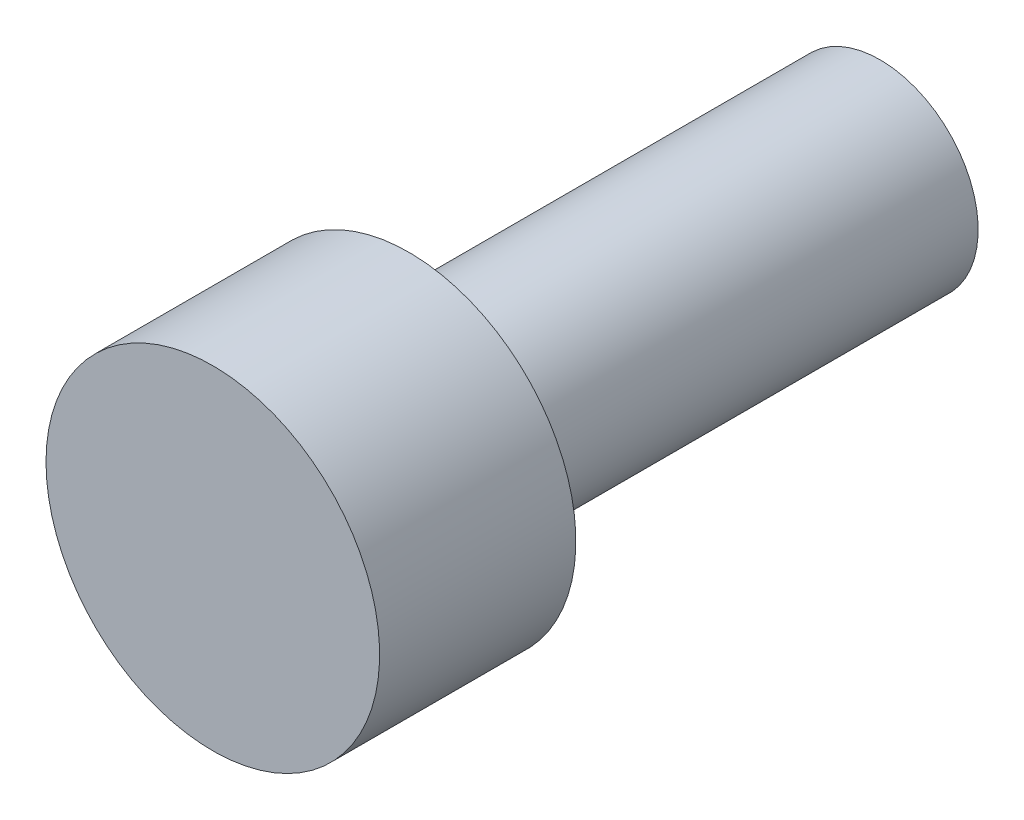
SolidWorks part; units mm, degrees
material "1.1191 (C45E)"
ref_plane "Front Plane" through (0, 0, 0) normal (0, 0, 1) x (1, 0, 0)
ref_plane "Top Plane" through (0, 0, 0) normal (0, 1, 0) x (1, 0, 0)
ref_plane "Right Plane" through (0, 0, 0) normal (1, 0, 0) x (0, 0, -1)
sketch "Sketch1" plane through (0, 0, 0) normal (0, 1, 0) x (1, 0, 0)
  line L0 (0, -5) -> (4.25, -5)
  line L1 (4.25, -5) -> (4.25, 0)
  line L2 (4.25, 0) -> (2.5, 0)
  line L3 (2.5, 0) -> (2.5, 12)
  line L4 (2.5, 12) -> (0, 12)
  line L5 (0, 12) -> (0, -5) construction
  line L6 (0, -5) -> (0, 12)
revolve "REV_ISO4762_M5x12_8.8" add sketch "Sketch1" angle 360 about L5
